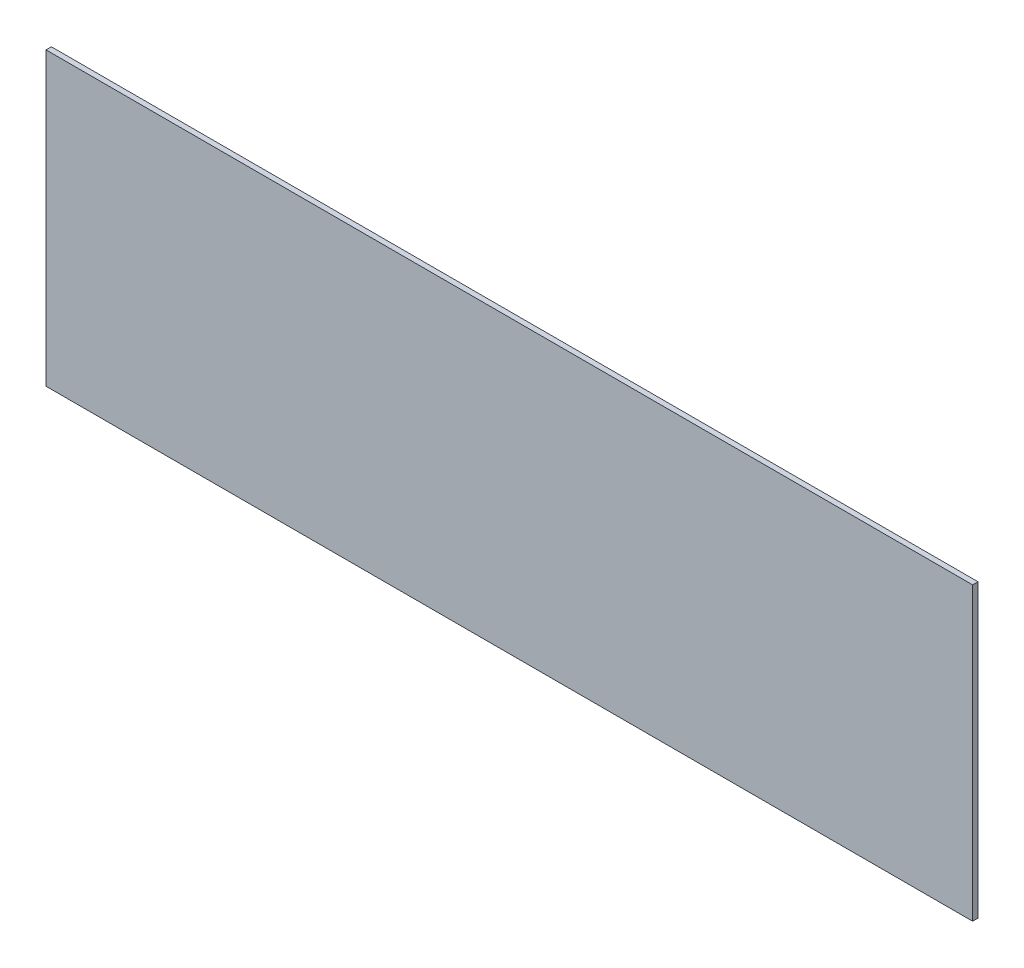
SolidWorks part; units mm, degrees
ref_plane "Front Plane" through (0, 0, 0) normal (0, 0, 1) x (1, 0, 0)
ref_plane "Top Plane" through (0, 0, 0) normal (0, 1, 0) x (1, 0, 0)
ref_plane "Right Plane" through (0, 0, 0) normal (1, 0, 0) x (0, 0, -1)
sketch "Sketch1" plane through (0, 0, 0) normal (0, 0, 1) x (1, 0, 0)
  line L1 (0, 0) -> (41.35, 0)
  line L2 (0, 0) -> (0, 13)
  line L3 (0, 13) -> (41.35, 13)
  line L4 (41.35, 0) -> (41.35, 13)
  dimension "D1" = 41.35
  dimension "D2" = 13
extrude "Boss-Extrude1" add sketch "Sketch1" along normal blind 0.24
